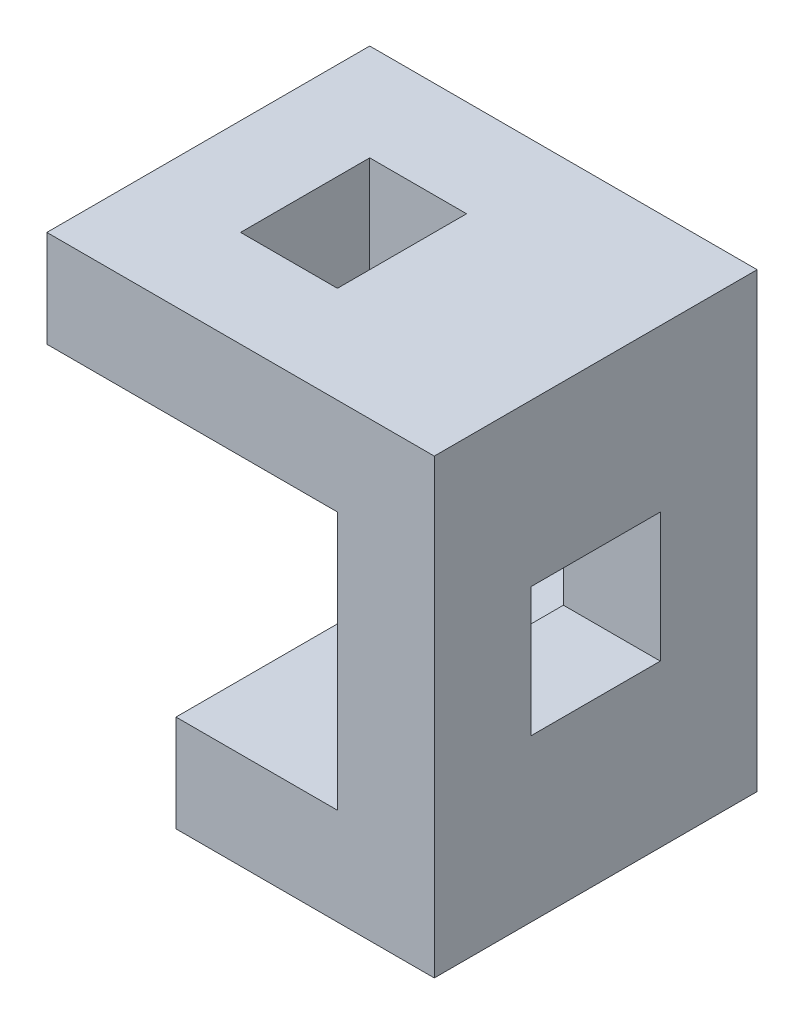
SolidWorks part; units mm, degrees
ref_plane "Plano frontal" through (0, 0, 0) normal (0, 0, 1) x (1, 0, 0)
ref_plane "Plano superior" through (0, 0, 0) normal (0, 1, 0) x (1, 0, 0)
ref_plane "Plano direito" through (0, 0, 0) normal (1, 0, 0) x (0, 0, -1)
sketch "Esboço1" plane through (0, 0, 0) normal (0, 0, 1) x (1, 0, 0)
  line L0 (-60, 0) -> (0, 0)
  line L1 (0, 0) -> (0, -70)
  line L2 (0, -70) -> (-40, -70)
  line L3 (-40, -70) -> (-40, -55)
  line L4 (-40, -55) -> (-15, -55)
  line L5 (-15, -55) -> (-15, -15)
  line L6 (-15, -15) -> (-60, -15)
  line L7 (-60, -15) -> (-60, 0)
  line L8 (-15, -25) -> (0, -25) construction
  line L9 (-15, -45) -> (0, -45) construction
  line L10 (-45, 0) -> (-45, -15) construction
  line L11 (-30, -15) -> (-30, 0) construction
  dimension "D1" = 60
  dimension "D2" = 15
  dimension "D3" = 15
  dimension "D4" = 40
  dimension "D5" = 15
  dimension "D6" = 70
  dimension "D7" = 20
  dimension "D8" = 15
  dimension "D9" = 15
extrude "Ressalto-extrusão1" add sketch "Esboço1" along normal blind 50
sketch "Esboço2" plane through (-15, 0, 0) normal (-1, 0, 0) x (0, 0, 1)
  line L0 (15, -25) -> (15, -45)
  line L1 (15, -45) -> (35, -45)
  line L2 (35, -45) -> (35, -25)
  line L3 (35, -25) -> (15, -25)
  line L4 (50, -70) -> (0, -70) construction
  line L5 (0, -15) -> (0, -55) construction
  dimension "D1" = 20
  dimension "D2" = 20
  dimension "D3" = 25
  dimension "D4" = 15
extrude "Corte-extrusão1" cut sketch "Esboço2" against normal blind 50
sketch "Esboço4" plane through (0, 0, 0) normal (0, 1, 0) x (1, 0, 0)
  line L0 (0, -15) -> (-20, -15) construction
  line L1 (0, -35) -> (-20, -35) construction
  line L2 (-20, -35) -> (-20, -15) construction
  line L3 (-20, 0) -> (-20, -50) construction
  line L4 (0, 0) -> (-60, 0) construction
  line L5 (0, -50) -> (-60, -50) construction
  line L10 (-45, -15) -> (-45, -35)
  line L11 (-45, -35) -> (-30, -35)
  line L12 (-30, -35) -> (-30, -15)
  line L13 (-30, -15) -> (-45, -15)
  line L14 (-60, -50) -> (-60, 0) construction
  dimension "D1" = 15
  dimension "D2" = 15
  dimension "D3" = 20
  dimension "D4" = 15
extrude "Corte-extrusão2" cut sketch "Esboço4" against normal blind 50
